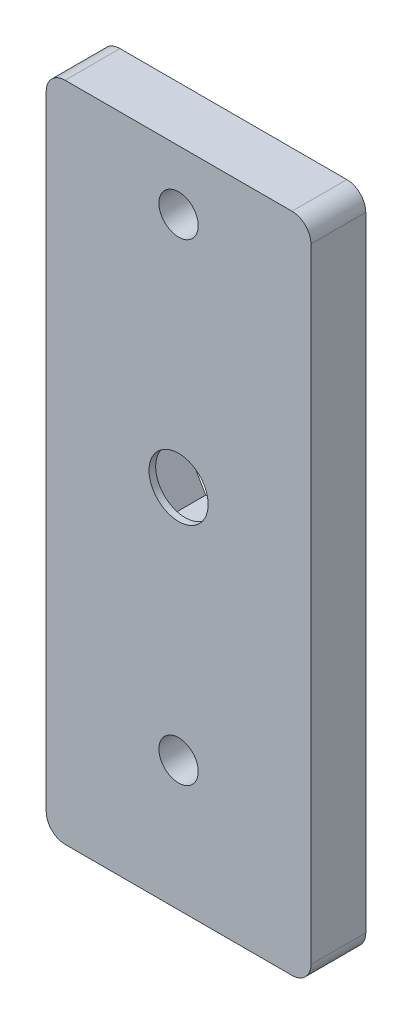
SolidWorks part; units mm, degrees
ref_plane "Front Plane" through (0, 0, 0) normal (0, 0, 1) x (1, 0, 0)
ref_plane "Top Plane" through (0, 0, 0) normal (0, 1, 0) x (1, 0, 0)
ref_plane "Right Plane" through (0, 0, 0) normal (1, 0, 0) x (0, 0, -1)
sketch "Sketch1" plane through (0, 0, 0) normal (0, 0, 1) x (1, 0, 0)
  line L1 (-13.9985, 34.998) -> (14, 34.998)
  line L2 (-13.9985, 34.998) -> (-13.9985, -35)
  line L3 (-13.9985, -35) -> (14, -35)
  line L4 (14, 34.998) -> (14, -35)
  circle A0 centre (0.0005, -21.295) radius 2.079
  circle A1 centre (0, 3.7036) radius 3.125
  circle A2 centre (0.0005, 28.705) radius 2.0789
  circle A4 centre (0.0005, -21.295) radius 2.079 construction
  circle A5 centre (0.0005, 28.705) radius 2.0789 construction
  dimension "D1" = 6.25
extrude "Boss-Extrude1" add sketch "Sketch1" along normal blind 5.8
sketch "Sketch2" plane through (0, 0, 0) normal (0, 0, -1) x (-1, 0, 0)
  line B0 (2.9288, 8.7763) -> (-2.9288, 8.7763)
  line B1 (-2.9288, 8.7763) -> (-5.8575, 3.7036)
  line B2 (-5.8575, 3.7036) -> (-2.9288, -1.3692)
  line B3 (-2.9288, -1.3692) -> (2.9288, -1.3692)
  line B4 (2.9288, -1.3692) -> (5.8575, 3.7036)
  line B5 (5.8575, 3.7036) -> (2.9288, 8.7763)
sketch_block_instance "M6 Nut-1"
sketch_block "M6 Nut" parameters "D1"=9.85
extrude "Cut-Extrude1" cut sketch "Sketch2" against normal blind 5.1
fillet "Fillet1" radius 2 4 edges at (14, -35, 2.9) (-13.9985, -35, 2.9) (14, 34.998, 2.9) (-13.9985, 34.998, 2.9)
